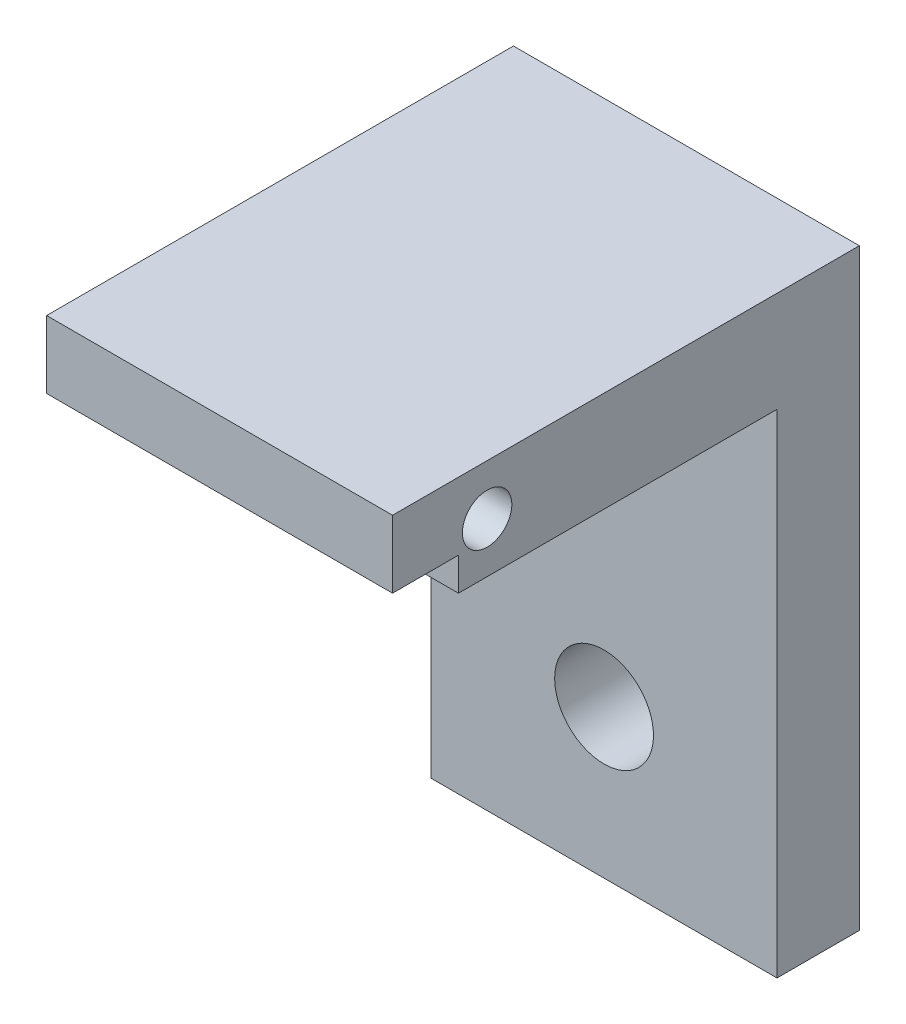
SolidWorks part; units mm, degrees
ref_plane "Front Plane" through (0, 0, 0) normal (0, 0, 1) x (1, 0, 0)
ref_plane "Top Plane" through (0, 0, 0) normal (0, 1, 0) x (1, 0, 0)
ref_plane "Right Plane" through (0, 0, 0) normal (1, 0, 0) x (0, 0, -1)
sketch "Sketch1" plane through (0, 0, 0) normal (0, 1, 0) x (1, 0, 0)
  line L1 (-5.25, -2.5) -> (5.25, -2.5)
  line L2 (-5.25, -2.5) -> (-5.25, 2.5)
  line L3 (-5.25, 2.5) -> (5.25, 2.5)
  line L4 (5.25, -2.5) -> (5.25, 2.5)
  line L5 (-5.25, -2.5) -> (5.25, 2.5) construction
  line L6 (-5.25, 2.5) -> (5.25, -2.5) construction
  point P0 (0, 0)
  dimension "D1" = 10.5
  dimension "D2" = 5
extrude "Boss-Extrude1" add sketch "Sketch1" along normal blind 18
sketch "Sketch2" plane through (0, 0, 2.5) normal (0, 0, 1) x (1, 0, 0)
  line L0 (5.25, 18) -> (5.25, 0) construction
  line L1 (-5.25, 18) -> (5.25, 18)
  line L2 (-5.25, 18) -> (-5.25, 13)
  line L3 (-5.25, 13) -> (5.25, 13)
  line L4 (5.25, 18) -> (5.25, 13)
  dimension "D1" = 5
extrude "Boss-Extrude2" add sketch "Sketch2" along normal blind 7.3
sketch "Sketch3" plane through (0, 0, 9.8) normal (0, 0, 1) x (1, 0, 0)
  line L0 (5.25, 13) -> (5.25, 18) construction
  line L1 (-5.25, 13) -> (5.25, 13)
  line L2 (-5.25, 13) -> (-5.25, 14.95)
  line L3 (-5.25, 14.95) -> (5.25, 14.95)
  line L4 (5.25, 13) -> (5.25, 14.95)
  dimension "D1" = 1.95
extrude "Cut-Extrude1" cut sketch "Sketch3" against normal blind 7.3
sketch "Sketch4" plane through (0, 0, 0) normal (0, -1, 0) x (-1, 0, 0)
  line L0 (-5.25, -2.5) -> (-5.25, 2.5) construction
  line L1 (5.25, 2.5) -> (-5.25, 2.5)
  line L2 (5.25, 2.5) -> (5.25, 0)
  line L3 (5.25, 0) -> (-5.25, 0)
  line L4 (-5.25, 2.5) -> (-5.25, 0)
  dimension "D1" = 2.5
extrude "Cut-Extrude2" cut sketch "Sketch4" against normal blind 26.3
sketch "Sketch5" plane through (0, 0, 0) normal (0, 0, -1) x (-1, 0, 0)
  line L0 (-5.25, 0) -> (5.25, 0) construction
  circle A0 centre (0, 4.5) radius 1.5
  dimension "D1" = 3
  dimension "D2" = 4.5
extrude "Cut-Extrude3" cut sketch "Sketch5" against normal blind 26.3
sketch "Sketch6" plane through (-5.25, 0, 0) normal (-1, 0, 0) x (0, 0, 1)
  line L0 (2.5, 14.95) -> (9.8, 14.95) construction
  line L1 (9.8, 18) -> (8.67, 18)
  line L2 (9.8, 18) -> (9.8, 14.95)
  line L3 (9.8, 14.95) -> (8.67, 14.95)
  line L4 (8.67, 18) -> (8.67, 14.95)
  dimension "D1" = 1.13
extrude "Cut-Extrude4" cut sketch "Sketch6" against normal blind 26.3
sketch "Sketch10" plane through (0, 0, 8.67) normal (0, 0, 1) x (1, 0, 0)
  line L1 (-5.25, 18) -> (5.25, 18)
  line L2 (-5.25, 18) -> (-5.25, 14.95)
  line L3 (-5.25, 14.95) -> (5.25, 14.95)
  line L4 (5.25, 18) -> (5.25, 14.95)
extrude "Boss-Extrude3" add sketch "Sketch10" along normal blind 5.5
sketch "Sketch11" plane through (-5.25, 0, 0) normal (-1, 0, 0) x (0, 0, 1)
  line L0 (14.17, 18) -> (14.17, 14.95) construction
  circle A0 centre (11.3, 16.475) radius 0.75
  dimension "D1" = 1.5
  dimension "D2" = 2.87
extrude "Cut-Extrude6" cut sketch "Sketch11" against normal blind 12.5
sketch "Sketch12" plane through (-5.25, 0, 0) normal (-1, 0, 0) x (0, 0, 1)
  line L1 (14.17, 14.95) -> (12.17, 14.95)
  line L2 (14.17, 14.95) -> (14.17, 15.95)
  line L3 (14.17, 15.95) -> (12.17, 15.95)
  line L4 (12.17, 14.95) -> (12.17, 15.95)
  dimension "D1" = 2
  dimension "D2" = 1
extrude "Cut-Extrude7" cut sketch "Sketch12" against normal blind 12.5
